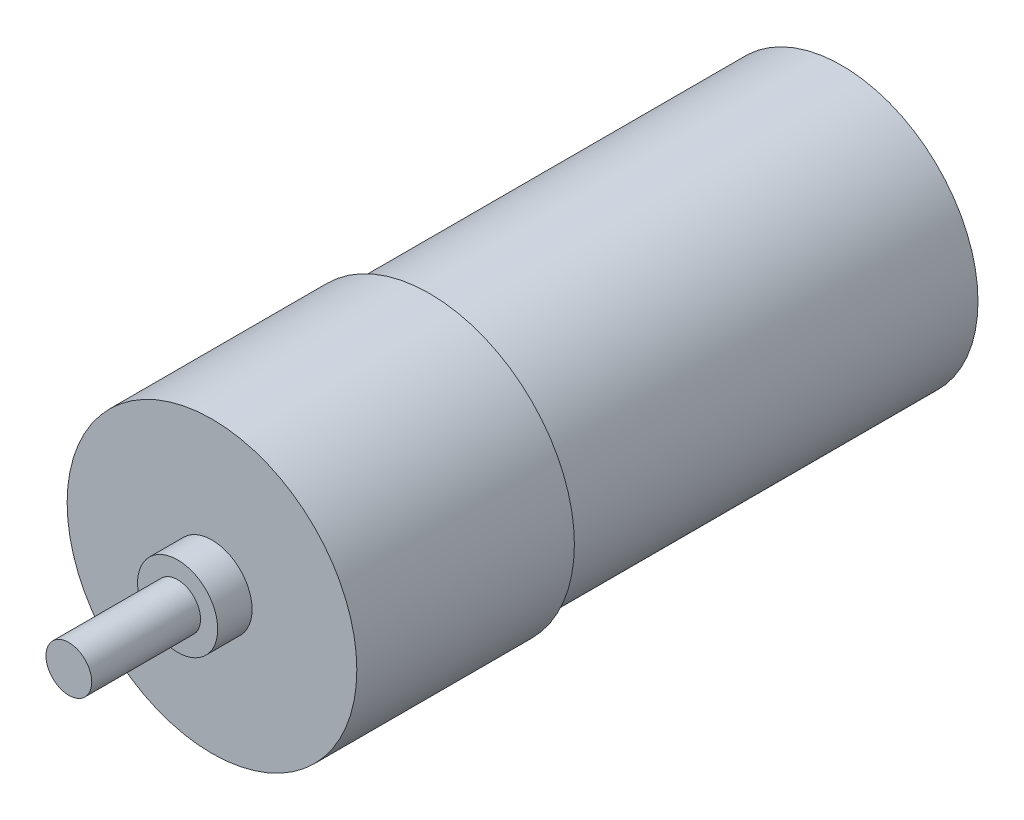
SolidWorks part; units mm, degrees
ref_plane "Front Plane" through (0, 0, 0) normal (0, 0, 1) x (1, 0, 0)
ref_plane "Top Plane" through (0, 0, 0) normal (0, 1, 0) x (1, 0, 0)
ref_plane "Right Plane" through (0, 0, 0) normal (1, 0, 0) x (0, 0, -1)
sketch "Sketch1" plane through (0, 0, 0) normal (0, 0, 1) x (1, 0, 0)
  circle A0 centre (0, 0) radius 11.9
  dimension "D1" = 23.8
extrude "Boss-Extrude1" add sketch "Sketch1" along normal blind 36
sketch "Sketch2" plane through (0, 0, 36) normal (0, 0, 1) x (1, 0, 0)
  circle A0 centre (0, 0) radius 12.65
  dimension "D1" = 25.3
extrude "Boss-Extrude2" add sketch "Sketch2" along normal blind 19
sketch "Sketch3" plane through (0, 0, 55) normal (0, 0, 1) x (1, 0, 0)
  circle A0 centre (0, 0) radius 3.5
  dimension "D1" = 7
extrude "Boss-Extrude3" add sketch "Sketch3" along normal blind 3
sketch "Sketch4" plane through (0, 0, 58) normal (0, 0, 1) x (1, 0, 0)
  circle A0 centre (0, 0) radius 2
  dimension "D1" = 4
extrude "Boss-Extrude4" add sketch "Sketch4" along normal blind 9.5
